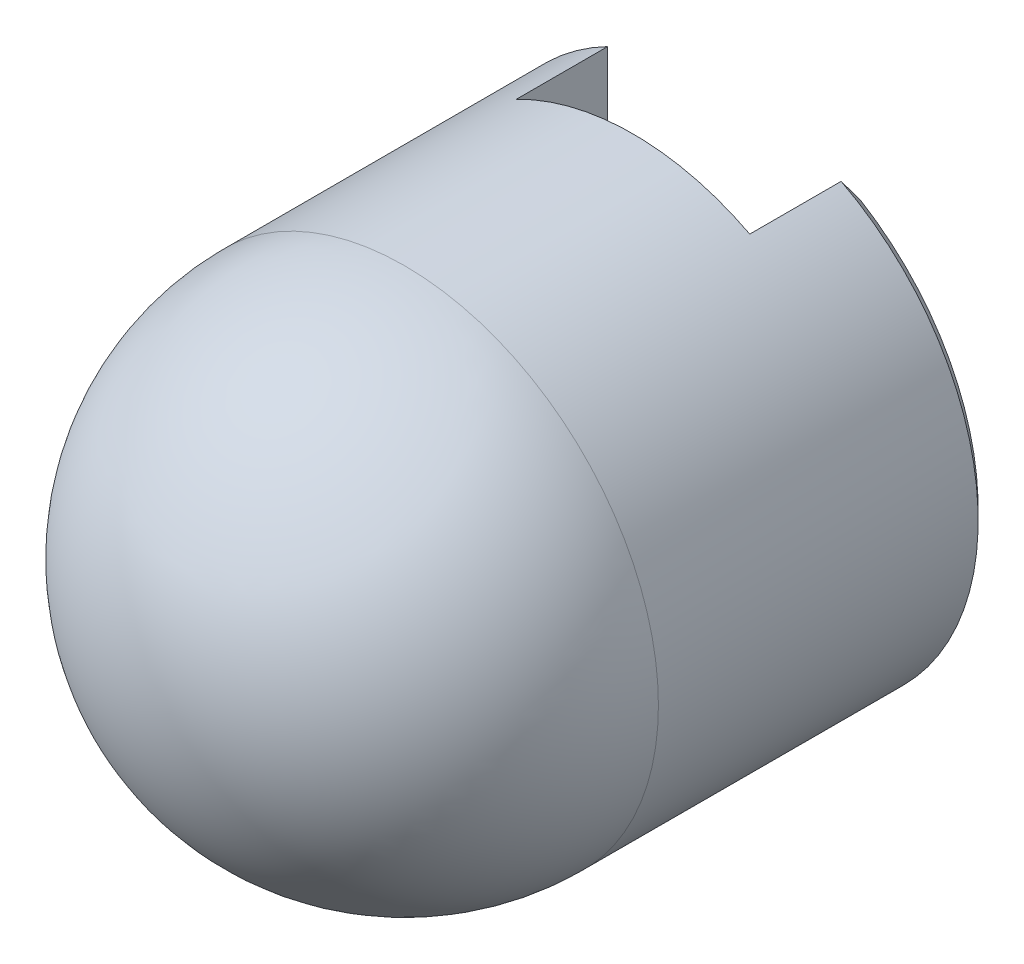
SolidWorks part; units mm, degrees
ref_plane "Front Plane" through (0, 0, 0) normal (0, 0, 1) x (1, 0, 0)
ref_plane "Top Plane" through (0, 0, 0) normal (0, 1, 0) x (1, 0, 0)
ref_plane "Right Plane" through (0, 0, 0) normal (1, 0, 0) x (0, 0, -1)
sketch "Sketch1" plane through (0, 0, 0) normal (0, 0, 1) x (1, 0, 0)
  circle A0 centre (0, 0) radius 5
  dimension "D1" = 10
extrude "Boss-Extrude1" add sketch "Sketch1" along normal blind 11.5
fillet "Fillet1" radius 5 1 edges at (5, 0, 11.5)
ref_plane "Plane1" through (0, 0, 1.2) normal (0, 0, -1) x (-1, 0, 0)
sketch "Sketch3" plane through (0, 0, 1.2) normal (0, 0, -1) x (-1, 0, 0)
  line L1 (4, -4) -> (-4, -4)
  line L2 (4, -4) -> (4, 4)
  line L3 (4, 4) -> (-4, 4)
  line L4 (-4, -4) -> (-4, 4)
  line L5 (4, -4) -> (-4, 4) construction
  line L6 (4, 4) -> (-4, -4) construction
  point P0 (0, 0)
  dimension "D1" = 8
  dimension "D2" = 8
extrude "Boss-Extrude2" [suppressed] add sketch "Sketch3" against normal blind 1.2
sketch "Sketch4" plane through (0, 0, 0) normal (0, 0, -1) x (-1, 0, 0)
  line L1 (2.3, 7.5) -> (-2.3, 7.5)
  line L2 (2.3, 7.5) -> (2.3, -7.5)
  line L3 (2.3, -7.5) -> (-2.3, -7.5)
  line L4 (-2.3, 7.5) -> (-2.3, -7.5)
  line L5 (2.3, 7.5) -> (-2.3, -7.5) construction
  line L6 (2.3, -7.5) -> (-2.3, 7.5) construction
  point P0 (0, 0)
  dimension "D1" = 4.6
  dimension "D2" = 15
extrude "Cut-Extrude1" cut sketch "Sketch4" against normal blind 2
chamfer "Chamfer1" distance 0.2 angle 45 4 edges at (2.3, 0, 0) (5, 0, 0) (-2.3, 0, 0) (-5, 0, 0)
